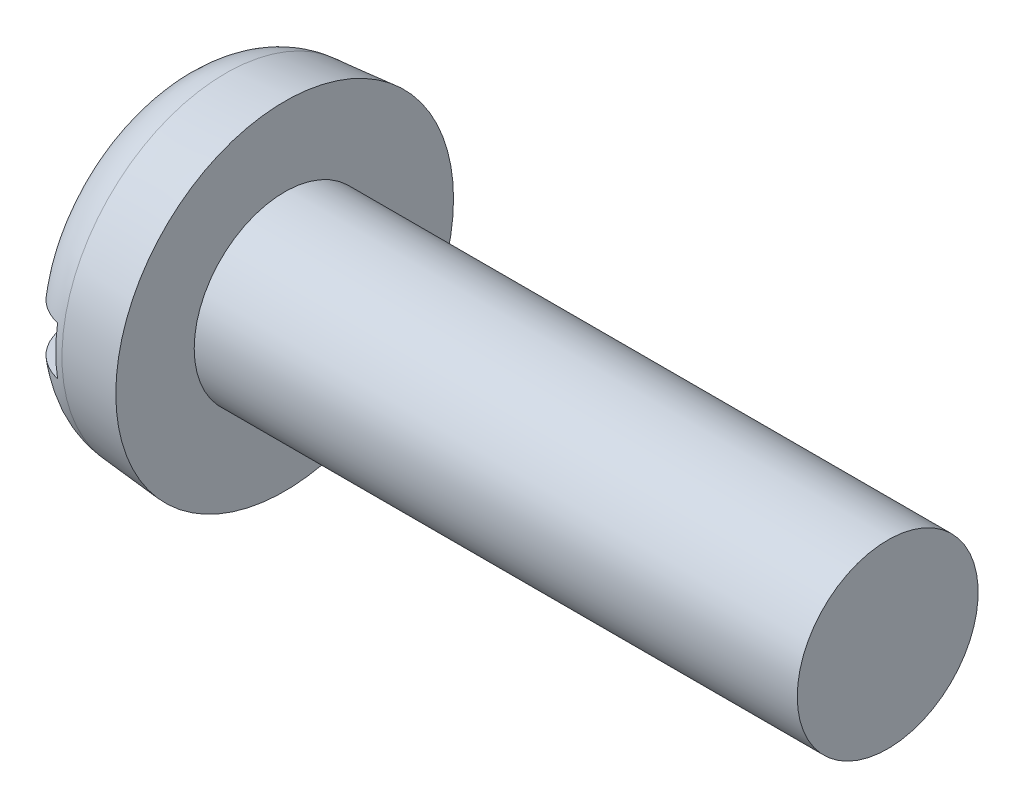
SolidWorks part; units mm, degrees
ref_plane "Plane1" through (0, 0, 0) normal (0, 0, 1) x (1, 0, 0)
ref_plane "Plane2" through (0, 0, 0) normal (0, 1, 0) x (1, 0, 0)
ref_plane "Plane3" through (0, 0, 0) normal (1, 0, 0) x (0, 0, -1)
sketch "BodySke" plane through (0, 0, 0) normal (0, 0, 1) x (1, 0, 0)
  line L0 (1.8, 1.5) -> (1.8, 2.8)
  line L1 (0, 0) -> (0, 2.6425)
  line L2 (-25.4, 0) -> (127, 0) construction
  line L3 (11.8, 0) -> (0, 0)
  line L4 (1.8, 1.5) -> (11.8, 1.5)
  line L5 (11.8, 1.5) -> (11.8, 0)
  line L6 (0, 2.6425) -> (1.8, 2.8)
  line L9 (2.3, 3.0875) -> (2.3, -6.4375) construction
  line L10 (1.8, 6.35) -> (1.8, -3.175) construction
  dimension "Length" = 10
  dimension "Head_ht" = 1.8
  dimension "Advance" = 0.5
  dimension "Thread_nom" = 10
  dimension "Head_dia" = 5.6
  dimension "Head_side_angle" = 5
  dimension "Diameter" = 3
revolve "Base-Revolve" add sketch "BodySke"
cosmetic thread "ThreadCosmetic" [suppressed]
fillet "Fillet1" [suppressed] radius 0.1
fillet "Fillet2" radius 0.9 1 edges at (0, 0, 2.6425)
sketch "Sketch2" plane through (0, 0, 0) normal (1, 0, 0) x (0, 0, -1)
  line L0 (2.8, -0.4) -> (-2.8, -0.4)
  line L1 (2.8, -0.4) -> (2.8, 0.4)
  line L2 (-2.8, 0.4) -> (2.8, 0.4)
  line L3 (-2.8, 0.4) -> (-2.8, -0.4)
  dimension "D1" = 5.6
  dimension "Slot_width" = 0.8
  dimension "D2" = 2.8
  dimension "D3" = 0.4
extrude "Slot" cut sketch "Sketch2" along normal blind 0.7
sketch "ThdSchSke" plane through (0, 0, 0) normal (0, 0, 1) x (1, 0, 0)
  line L0 (2.8, -1.2195) -> (2.6036, -1.5)
  line L1 (2.8, -1.2195) -> (2.9964, -1.5)
  line L2 (2.9964, -1.5) -> (2.9964, -1.875)
  line L3 (-3.175, 0) -> (5.1513, 0) construction
  line L5 (2.9964, -1.875) -> (2.6036, -1.875)
  line L6 (2.6036, -1.875) -> (2.6036, -1.5)
  dimension "Diameter" = 3
  dimension "SideAngle" = 55
  dimension "VeeAngle" = 70
  dimension "Thread_minor" = 2.439
  dimension "Overcut" = 3.75
  dimension "Start" = 2.8
revolve "ThreadSchematic" [suppressed] cut sketch "ThdSchSke" angle 360 about L3
pattern_linear "ThdSchPat" [suppressed]
equation "\"D1@Sketch2\" = \"Head_dia@BodySke\""
equation "\"D2@Sketch2\" = \"D1@Sketch2\" / 2"
equation "\"D3@Sketch2\" = \"Slot_width@Sketch2\" / 2"
equation "\"Thread_length@ThreadCosmetic\" = ((sgn( (\"Length@BodySke\" - \"Advance@BodySke\" * 2.0 ) - \"Thread_nom@BodySke\" )-1)*( (\"Length@BodySke\" - \"Advance@BodySke\"  * 2.0) - \"Thread_nom@BodySke\" ))/-2+ \"Thread_nom@BodySke\""
equation "\"Thread_minor@ThdSchSke\" = \"Thread_minor@ThreadCosmetic\""
equation "\"Diameter@ThdSchSke\" = \"Diameter@BodySke\""
equation "\"Overcut@ThdSchSke\" = \"Diameter@BodySke\" * 1.25"
equation "\"Start@ThdSchSke\" = \"Head_ht@BodySke\" + \"Length@BodySke\" - \"Thread_length@ThreadCosmetic\"  '---Non-countersunk---"
equation "\"Num_threads@ThdSchPat\" = int( \"Thread_length@ThreadCosmetic\" / \"Advance@BodySke\" + 0.999 )  + 1"
equation "\"Advance@ThdSchPat\" = \"Thread_length@ThreadCosmetic\" /  (\"Num_threads@ThdSchPat\" - 1) 'relax it"
